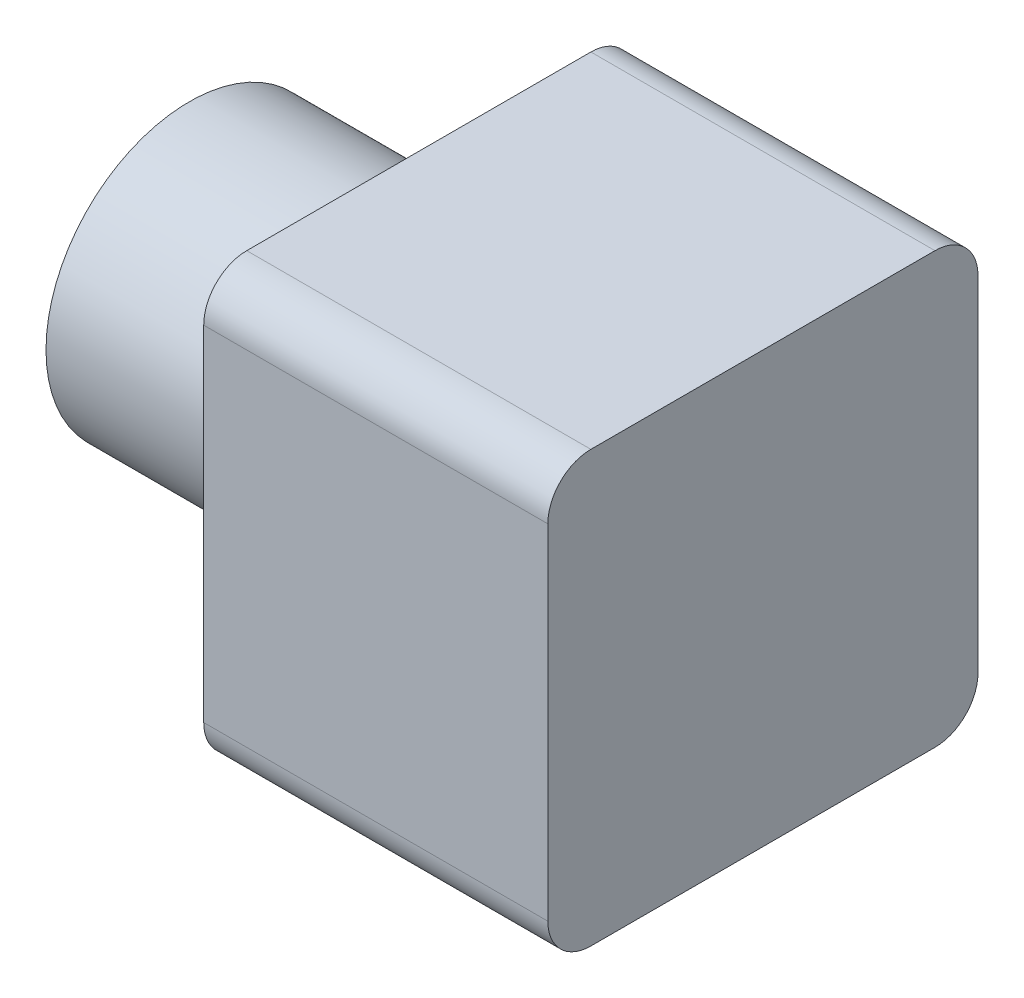
SolidWorks part; units mm, degrees
ref_plane "Front Plane" through (0, 0, 0) normal (0, 0, 1) x (1, 0, 0)
ref_plane "Top Plane" through (0, 0, 0) normal (0, 1, 0) x (1, 0, 0)
ref_plane "Right Plane" through (0, 0, 0) normal (1, 0, 0) x (0, 0, -1)
sketch "Sketch2" plane through (-36.1378, 0, 0) normal (-1, 0, 0) x (0, 0, 1)
  circle A0 centre (-25, -31.6006) radius 5
extrude "Boss-Extrude1" add sketch "Sketch2" along normal blind 8
sketch "Sketch3" plane through (-36.1378, 0, 0) normal (1, 0, 0) x (0, 0, -1)
  line L1 (17.5, -24.1006) -> (32.5, -24.1006)
  line L2 (17.5, -24.1006) -> (17.5, -39.1006)
  line L3 (17.5, -39.1006) -> (32.5, -39.1006)
  line L4 (32.5, -24.1006) -> (32.5, -39.1006)
  circle A0 centre (25, -31.6006) radius 5 construction
  dimension "D1" = 7.5
  dimension "D2" = 15
  dimension "D3" = 7.5
  dimension "D4" = 15
extrude "Boss-Extrude2" add sketch "Sketch3" along normal blind 12
sketch "Sketch4" plane through (-44.1378, 0, 0) normal (-1, 0, 0) x (0, 0, 1)
  circle A2 centre (-25, -31.6006) radius 4
  circle A3 centre (-25, -31.6006) radius 4
  dimension "D1" = 1
extrude "Cut-Extrude1" cut sketch "Sketch4" against normal blind 1
fillet "Fillet1" radius 1.5
